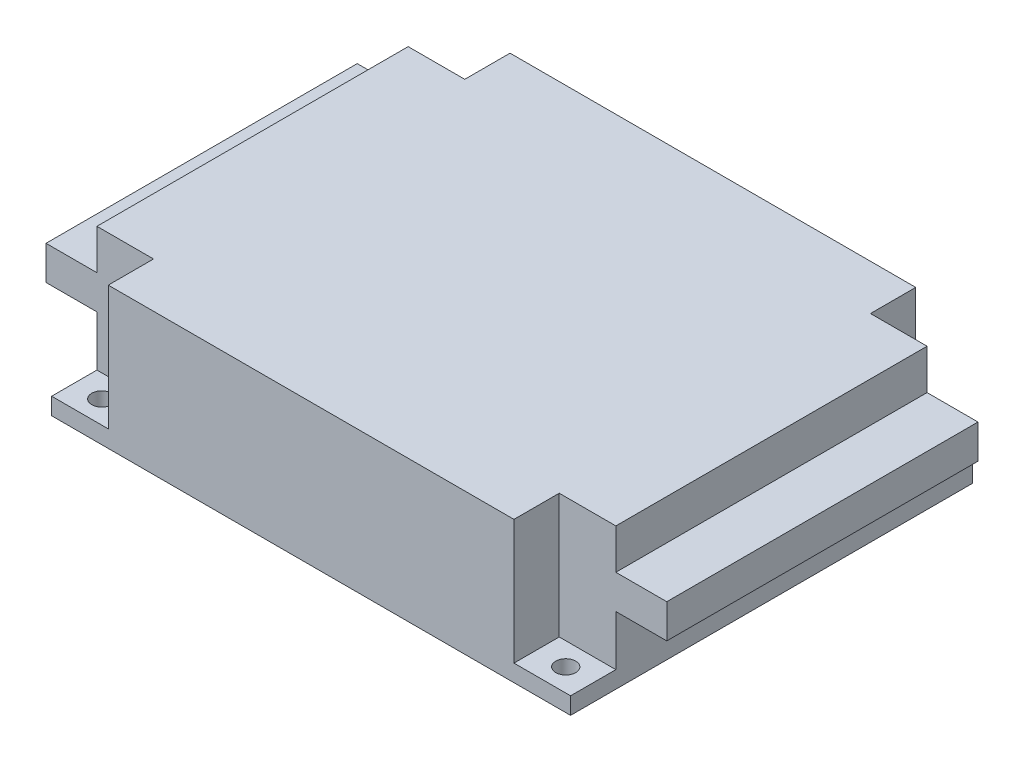
SolidWorks part; units mm, degrees
ref_plane "前视基准面" through (0, 0, 0) normal (0, 0, 1) x (1, 0, 0)
ref_plane "上视基准面" through (0, 0, 0) normal (0, 1, 0) x (1, 0, 0)
ref_plane "右视基准面" through (0, 0, 0) normal (1, 0, 0) x (0, 0, -1)
ref_plane "基准面1" through (0, 25, 0) normal (0, 1, 0) x (1, 0, 0)
sketch "草图1" plane through (0, 25, 0) normal (0, 1, 0) x (1, 0, 0)
  line L0 (91.7, 60) -> (0, 60)
  line L1 (0, 60) -> (0, -11)
  line L2 (0, -11) -> (91.7, -11)
  line L3 (91.7, -11) -> (91.7, 60)
extrude "凸台-拉伸1" add sketch "草图1" against normal blind 25
sketch "草图2" plane through (0, 0, -60) normal (0, 0, -1) x (-1, 0, 0)
  line L0 (-10.0029, 25) -> (-10.0029, 3)
  line L1 (-10.0029, 3) -> (0, 3)
  line L2 (0, 3) -> (0, 25)
  line L3 (0, 25) -> (-10.0029, 25)
extrude "切除-拉伸1" cut sketch "草图2" against normal blind 8.0003
sketch "草图3" plane through (0, 0, 0) normal (-1, 0, 0) x (0, 0, 1)
  line L0 (2.9997, 25) -> (2.9997, 11.9)
  line L1 (2.9997, 11.9) -> (-51.9997, 11.9)
  line L2 (-51.9997, 11.9) -> (-51.9997, 25)
  line L3 (-51.9997, 25) -> (2.9997, 25)
extrude "凸台-拉伸2" add sketch "草图3" along normal blind 9
sketch "草图4" plane through (0, 0, 0) normal (-1, 0, 0) x (0, 0, 1)
  line L0 (2.9997, 25) -> (2.9997, 3)
  line L1 (2.9997, 3) -> (11, 3)
  line L2 (11, 3) -> (11, 25)
  line L3 (11, 25) -> (2.9997, 25)
extrude "切除-拉伸2" cut sketch "草图4" against normal blind 10.0029
sketch "草图5" plane through (91.7, 0, 0) normal (1, 0, 0) x (0, 0, -1)
  line L0 (51.9997, 3) -> (60, 3)
  line L1 (60, 3) -> (60, 25)
  line L2 (60, 25) -> (51.9997, 25)
  line L3 (51.9997, 25) -> (51.9997, 3)
extrude "切除-拉伸3" cut sketch "草图5" against normal blind 10.0029
sketch "草图6" plane through (91.7, 0, 0) normal (1, 0, 0) x (0, 0, -1)
  line L0 (51.9997, 11.9) -> (-2.9997, 11.9)
  line L1 (-2.9997, 11.9) -> (-2.9997, 25)
  line L2 (-2.9997, 25) -> (51.9997, 25)
  line L3 (51.9997, 25) -> (51.9997, 11.9)
extrude "凸台-拉伸3" add sketch "草图6" along normal blind 9
sketch "草图7" plane through (91.7, 0, 0) normal (1, 0, 0) x (0, 0, -1)
  line L0 (-11, 3) -> (-2.9997, 3)
  line L1 (-2.9997, 3) -> (-2.9997, 25)
  line L2 (-2.9997, 25) -> (-11, 25)
  line L3 (-11, 25) -> (-11, 3)
extrude "切除-拉伸4" cut sketch "草图7" against normal blind 10.0029
sketch "草图8" plane through (0, 0, -51.9997) normal (0, 0, -1) x (-1, 0, 0)
  line L0 (9, 25) -> (0, 25)
  line L1 (0, 25) -> (0, 17.9)
  line L2 (0, 17.9) -> (9, 17.9)
  line L3 (9, 17.9) -> (9, 25)
extrude "切除-拉伸5" cut sketch "草图8" against normal through all
sketch "草图9" plane through (0, 0, 2.9997) normal (0, 0, 1) x (1, 0, 0)
  line L0 (91.7, 25) -> (91.7, 17.9)
  line L1 (91.7, 17.9) -> (100.7, 17.9)
  line L2 (100.7, 17.9) -> (100.7, 25)
  line L3 (100.7, 25) -> (91.7, 25)
extrude "切除-拉伸6" cut sketch "草图9" against normal through all
hole_wizard "M3 间隙孔1" positions "草图11" profile "草图10" hole size "M3" standard "ANSI Metric"
sketch "草图11" plane through (0, 0, 0) normal (0, -1, 0) x (-1, 0, 0)
  point P0 (-86.8463, 55.9996)
  point P1 (-86.8463, -6.9996)
  point P2 (-4.8537, -6.9996)
  point P3 (-4.8537, 55.9996)
sketch "草图10" plane through (86.8463, 0, -55.9996) normal (1, 0, 0) x (0, 0, -1)
  line L0 (0, 0) -> (0, 25)
  line L1 (0, 25) -> (1.7656, 25)
  line L2 (1.7656, 25) -> (1.7656, 0)
  line L5 (1.7656, 0) -> (0, 0)
  line L11 (0, -6.35) -> (0, 107.95) construction
  dimension "通孔孔直径" = 3.5312
  dimension "通孔孔深度" = 25
